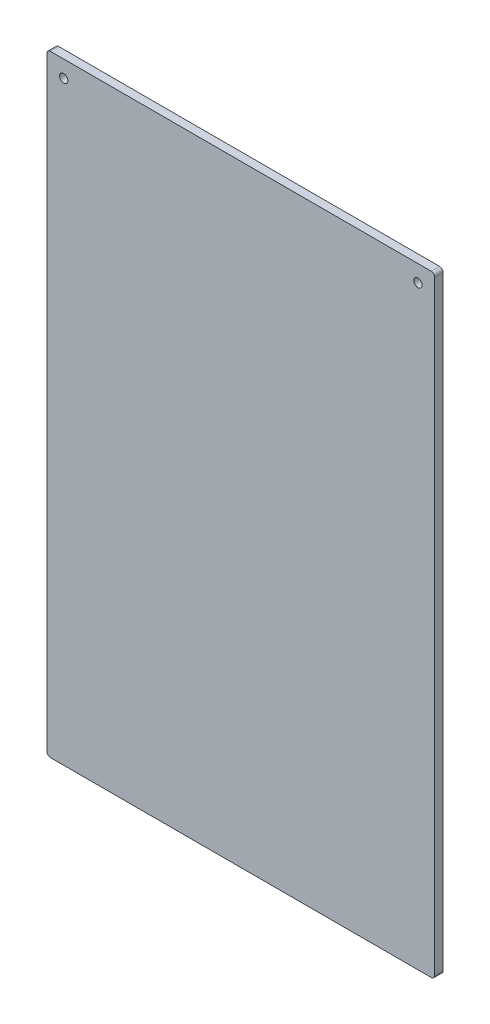
SolidWorks part; units mm, degrees
ref_plane "Front Plane" through (0, 0, 0) normal (0, 0, 1) x (1, 0, 0)
ref_plane "Top Plane" through (0, 0, 0) normal (0, 1, 0) x (1, 0, 0)
ref_plane "Right Plane" through (0, 0, 0) normal (1, 0, 0) x (0, 0, -1)
sketch "Sketch1" plane through (0, 0, 0) normal (0, 0, 1) x (1, 0, 0)
  line L0 (0, 0) -> (294.64, 0)
  line L1 (0, 0) -> (0, 464.82)
  line L2 (294.64, 0) -> (294.64, 464.82)
  line L3 (0, 464.82) -> (294.64, 464.82)
  circle A0 centre (12.7, 452.12) radius 3.175
  circle A1 centre (281.94, 452.12) radius 3.175
  point P9 (0, 0)
  dimension "D6" = 6.35
  dimension "D1" = 464.82
  dimension "D2" = 294.64
  dimension "D3" = 12.7
  dimension "D4" = 12.7
  dimension "D5" = 12.7
extrude "Boss-Extrude1" add sketch "Sketch1" along normal blind 6.35
fillet "Fillet1" radius 2.54 4 edges at (0, 464.82, 3.175) (0, 0, 3.175) (294.64, 0, 3.175) (294.64, 464.82, 3.175)
